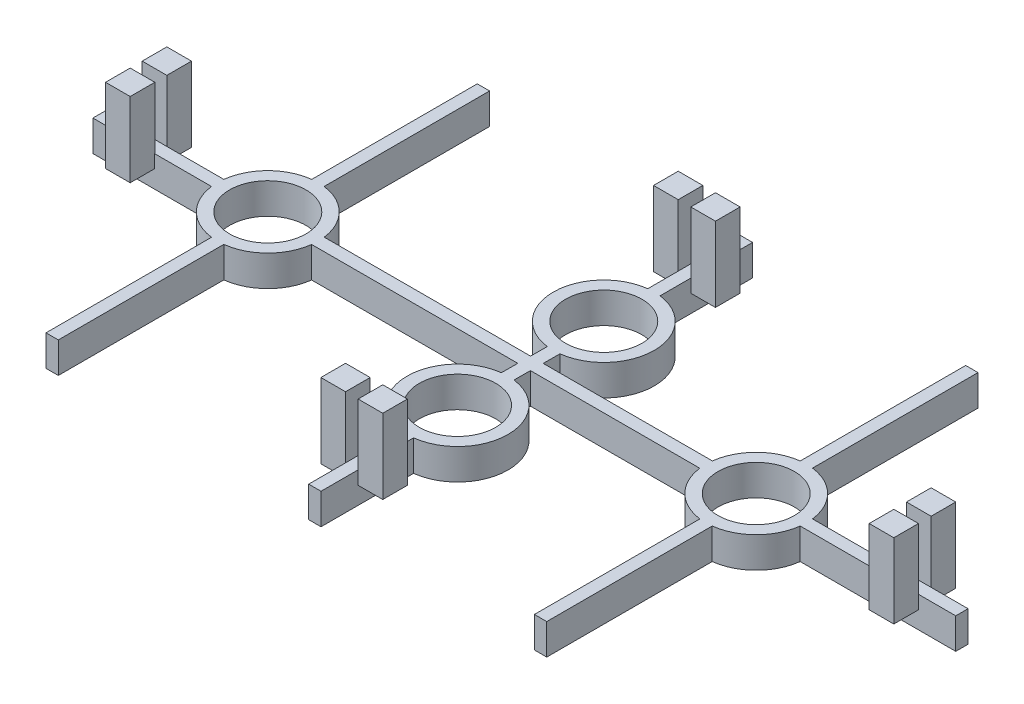
SolidWorks part; units mm, degrees
ref_plane "Front Plane" through (0, 0, 0) normal (0, 0, 1) x (1, 0, 0)
ref_plane "Top Plane" through (0, 0, 0) normal (0, 1, 0) x (1, 0, 0)
ref_plane "Right Plane" through (0, 0, 0) normal (1, 0, 0) x (0, 0, -1)
sketch "Sketch2" plane through (0, 0, 0) normal (0, 1, 0) x (1, 0, 0)
  line L0 (1.0181, -1.0218) -> (28.4777, -1)
  line L1 (-1.0002, 3.7343) -> (-1.0182, 1.0266)
  line L3 (1.0181, -1.0218) -> (1.0004, -3.681)
  line L4 (-34.4777, -1.05) -> (-1.0319, -1.0234)
  line L5 (1.0498, 3.7345) -> (1.0318, 1.0282)
  line L6 (-34.4777, 1) -> (-1.0182, 1.0266)
  line L7 (1.0318, 1.0282) -> (28.4777, 1.05)
  line L8 (-1.0319, -1.0234) -> (-1.0496, -3.6812)
  line L17 (-50.7522, 0.975) -> (-70, 0.975)
  line L18 (-41.6134, 8.1138) -> (-41.6134, 34.975)
  line L19 (-43.6134, -8.1638) -> (-43.6134, -35.025)
  line L20 (-1.0232, -19.9557) -> (-1.0232, -34.975)
  line L21 (1.0234, 20.009) -> (1.0234, 35.025)
  line L22 (37.6134, 8.1638) -> (37.6134, 35.025)
  line L23 (44.7522, -0.975) -> (70, -0.975)
  line L24 (35.6134, -8.1138) -> (35.6134, -34.975)
  line L25 (-50.7522, -1.025) -> (-70, -1.025)
  line L26 (-43.6134, 8.1138) -> (-43.6134, 34.975)
  line L27 (-41.6134, -8.1638) -> (-41.6134, -35.025)
  line L28 (0.9768, -19.9555) -> (0.9768, -34.975)
  line L29 (-0.9766, 20.0088) -> (-0.9766, 35.025)
  line L30 (35.6134, 8.1638) -> (35.6134, 35.025)
  line L31 (44.7522, 1.025) -> (70, 1.025)
  line L32 (37.6134, -8.1138) -> (37.6134, -34.975)
  line L33 (-70, 0.975) -> (-70, -1.025)
  line L34 (-43.6134, -35.025) -> (-41.6134, -35.025)
  line L35 (-1.0232, -34.975) -> (0.9768, -34.975)
  line L36 (35.6134, -34.975) -> (37.6134, -34.975)
  line L37 (-43.6134, 34.975) -> (-41.6134, 34.975)
  line L38 (-0.9766, 35.025) -> (1.0234, 35.025)
  line L39 (35.6134, 35.025) -> (37.6134, 35.025)
  line L40 (70, 1.025) -> (70, -0.975)
  circle A4 centre (-42.6134, -0.025) radius 6.2
  circle A5 centre (0.0241, 11.8701) radius 6.2
  circle A6 centre (36.6134, 0.025) radius 6.2
  circle A7 centre (-0.0239, -11.8168) radius 6.2
  arc A8 (1.0498, 3.7345) -> (1.0234, 20.009) centre (0.0241, 11.8701) ccw
  arc A9 (-34.4777, 1) -> (-41.6134, 8.1138) centre (-42.6134, -0.025) ccw
  arc A10 (28.4777, -1) -> (35.6134, -8.1138) centre (36.6134, 0.025) ccw
  arc A11 (-1.0496, -3.6812) -> (-1.0232, -19.9557) centre (-0.0239, -11.8168) ccw
  circle A12 centre (36.6134, 0.025) radius 8.2 construction
  circle A13 centre (-42.6134, -0.025) radius 8.2 construction
  circle A14 centre (0.0241, 11.8701) radius 8.2 construction
  circle A15 centre (-0.0239, -11.8168) radius 8.2 construction
  arc A16 (-50.7522, -1.025) -> (-43.6134, -8.1638) centre (-42.6134, -0.025) ccw
  arc A17 (-41.6134, -8.1638) -> (-34.4777, -1.05) centre (-42.6134, -0.025) ccw
  arc A18 (-43.6134, 8.1138) -> (-50.7522, 0.975) centre (-42.6134, -0.025) ccw
  arc A19 (-0.9766, 20.0088) -> (-1.0002, 3.7343) centre (0.0241, 11.8701) ccw
  arc A20 (0.9768, -19.9555) -> (1.0004, -3.681) centre (-0.0239, -11.8168) ccw
  arc A21 (35.6134, 8.1638) -> (28.4777, 1.05) centre (36.6134, 0.025) ccw
  arc A22 (37.6134, -8.1138) -> (44.7522, -0.975) centre (36.6134, 0.025) ccw
  arc A23 (44.7522, 1.025) -> (37.6134, 8.1638) centre (36.6134, 0.025) ccw
  point P4 (0, 0)
  point P8 (36.415, 0)
  point P9 (0, 0)
  point P11 (-42.415, 0)
  point P17 (0, -4)
  dimension "D1" = 12.4
  dimension "D4" = 12.4
  dimension "D5" = 2
  dimension "D2" = 12.4
  dimension "D3" = 12.4
extrude "Boss-Extrude1" add sketch "Sketch2" along normal blind 5
sketch "Sketch3" plane through (0, 5, 0) normal (0, 1, 0) x (1, 0, 0)
  point P7 (0, 0)
sketch "Sketch4" plane through (0, 5, 0) normal (0, 1, 0) x (1, 0, 0)
  line L0 (1.0234, 20.009) -> (1.0234, 35.025) construction
  line L1 (1.0234, 29) -> (5.0234, 29)
  line L2 (1.0234, 29) -> (1.0234, 25)
  line L3 (1.0234, 25) -> (5.0234, 25)
  line L4 (5.0234, 29) -> (5.0234, 25)
  line L5 (-50.7522, 0.975) -> (-70, 0.975) construction
  line L6 (-60, 0.975) -> (-64, 0.975)
  line L7 (-60, 0.975) -> (-60, 4.975)
  line L8 (-60, 4.975) -> (-64, 4.975)
  line L9 (-64, 0.975) -> (-64, 4.975)
  line L10 (-72.8147, 0) -> (71.062, 0) construction
  line L11 (0, 0) -> (0, 40.7093) construction
  line L12 (70, 1.025) -> (44.7522, 1.025) construction
  line L13 (64, 1.025) -> (60, 1.025)
  line L14 (64, 1.025) -> (64, 5.025)
  line L15 (64, 5.025) -> (60, 5.025)
  line L16 (60, 1.025) -> (60, 5.025)
  line L17 (64, -5.025) -> (60, -5.025)
  line L18 (60, -1.025) -> (60, -5.025)
  line L19 (64, -1.025) -> (60, -1.025)
  line L20 (64, -1.025) -> (64, -5.025)
  line L21 (-1.0234, 25) -> (-5.0234, 25)
  line L22 (-5.0234, 29) -> (-5.0234, 25)
  line L23 (-1.0234, 29) -> (-5.0234, 29)
  line L24 (-1.0234, 29) -> (-1.0234, 25)
  line L25 (1.0234, -25) -> (5.0234, -25)
  line L26 (5.0234, -29) -> (5.0234, -25)
  line L27 (1.0234, -29) -> (5.0234, -29)
  line L28 (1.0234, -29) -> (1.0234, -25)
  line L29 (-1.0234, -29) -> (-1.0234, -25)
  line L30 (-1.0234, -29) -> (-5.0234, -29)
  line L31 (-5.0234, -29) -> (-5.0234, -25)
  line L32 (-1.0234, -25) -> (-5.0234, -25)
  line L33 (-60, -4.975) -> (-64, -4.975)
  line L34 (-64, -0.975) -> (-64, -4.975)
  line L35 (-60, -0.975) -> (-64, -0.975)
  line L36 (-60, -0.975) -> (-60, -4.975)
  dimension "D1" = 60
  dimension "D2" = 25
  dimension "D3" = 4
  dimension "D4" = 4
  dimension "D5" = 4
  dimension "D6" = 4
  dimension "D7" = 60
  dimension "D8" = 4
  dimension "D9" = 4
extrude "Boss-Extrude2" add sketch "Sketch4" along normal blind 10 and the other way blind 2.1322
